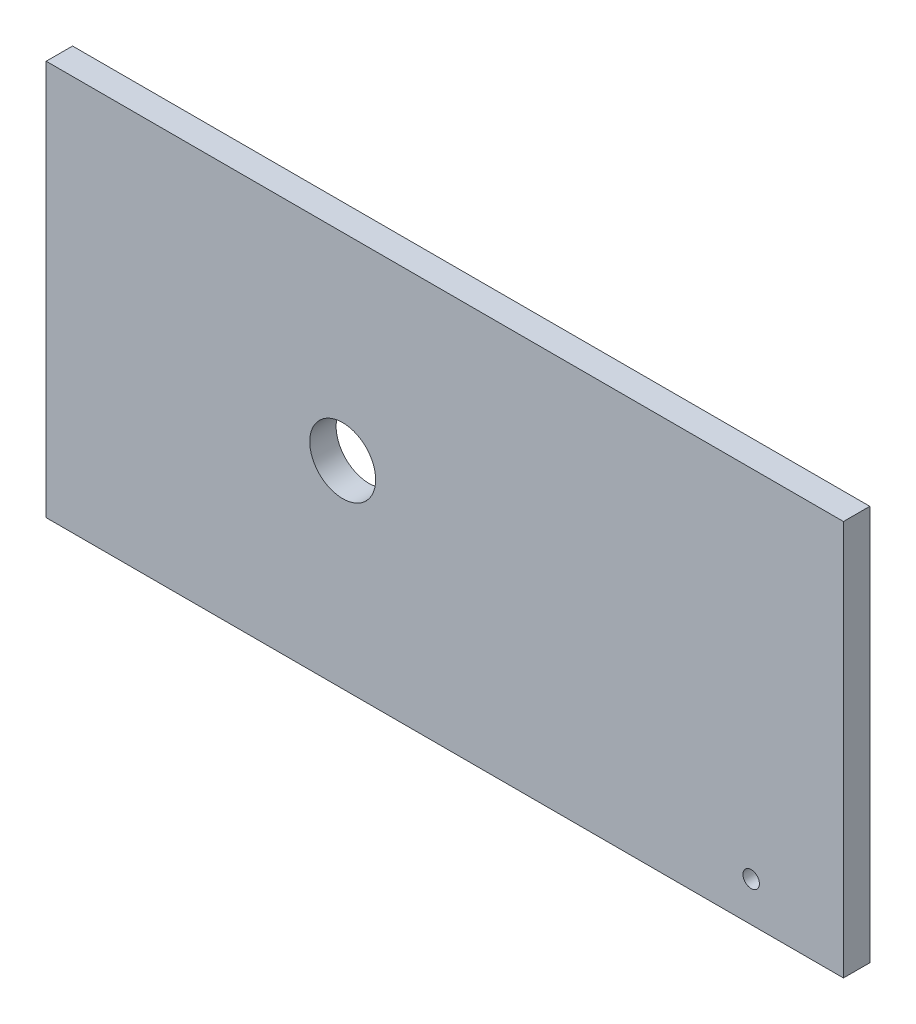
SolidWorks part; units mm, degrees
ref_plane "Front Plane" through (0, 0, 0) normal (0, 0, 1) x (1, 0, 0)
ref_plane "Top Plane" through (0, 0, 0) normal (0, 1, 0) x (1, 0, 0)
ref_plane "Right Plane" through (0, 0, 0) normal (1, 0, 0) x (0, 0, -1)
sketch "Sketch1" plane through (0, 0, 0) normal (0, 0, 1) x (1, 0, 0)
  line L1 (-81, -30) -> (40, -30)
  line L2 (-81, -30) -> (-81, 30)
  line L3 (-81, 30) -> (40, 30)
  line L11 (40, 30) -> (40, -30)
  circle A3 centre (-36, 0) radius 5
  circle A4 centre (26, -24) radius 1.25
  point P9 (-81, 0)
  dimension "D3" = 121
  dimension "D4" = 2.5
  dimension "D5" = 6
  dimension "D6" = 10
  dimension "D7" = 107
  dimension "D2" = 60
  dimension "D10" = 0
  dimension "D11" = 45
extrude "Boss-Extrude1" add sketch "Sketch1" along normal blind 4
